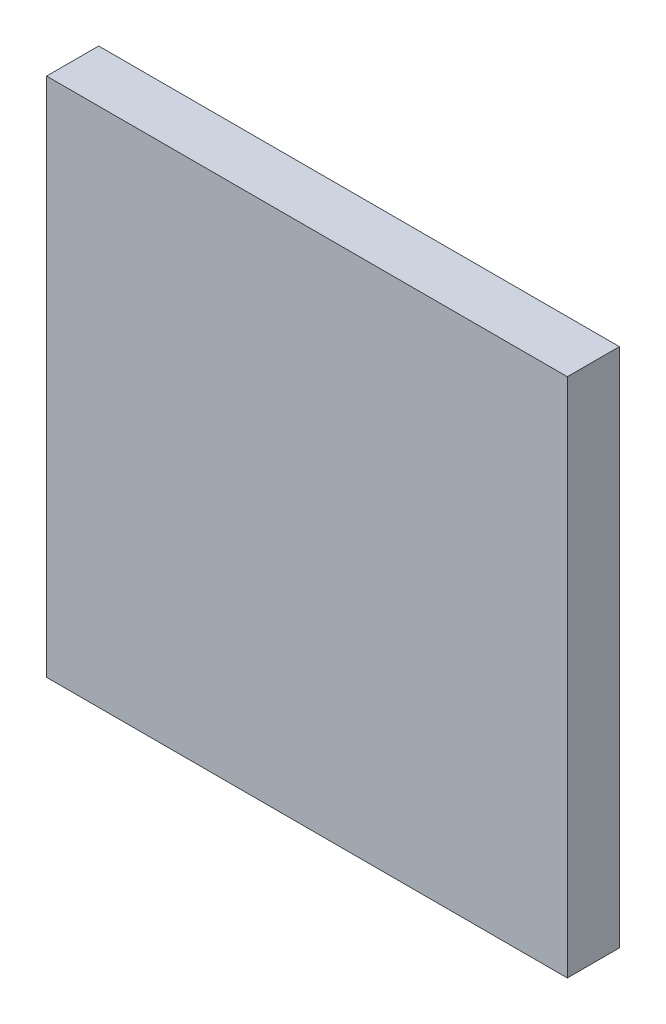
SolidWorks part; units mm, degrees
ref_plane "Plan de face" through (0, 0, 0) normal (0, 0, 1) x (1, 0, 0)
ref_plane "Plan de dessus" through (0, 0, 0) normal (0, 1, 0) x (1, 0, 0)
ref_plane "Plan de droite" through (0, 0, 0) normal (1, 0, 0) x (0, 0, -1)
sketch "Esquisse1" plane through (0, 0, 0) normal (0, 0, 1) x (1, 0, 0)
  line L1 (0, 0) -> (30, 0)
  line L2 (0, 0) -> (0, -30)
  line L3 (0, -30) -> (30, -30)
  line L4 (30, 0) -> (30, -30)
  dimension "D1" = 30
  dimension "D2" = 30
extrude "Boss.-Extru.1" add sketch "Esquisse1" along normal blind 3
ref_plane "Plan1" through (15, 0, 0) normal (-1, 0, 0) x (0, 0, 1)
sketch "Esquisse4" plane through (15, 0, 0) normal (-1, 0, 0) x (0, 0, 1)
  line L0 (0, 0) -> (0, -30) construction
  line L1 (0, -12.1733) -> (0, -13.6733)
  line L2 (0, -16.84) -> (0, -18.34)
  arc A0 (0, -12.1733) -> (0, -18.34) centre (-2.5481, -15.2567) ccw
  arc A1 (0, -13.6733) -> (0, -16.84) centre (-2.5481, -15.2567) ccw
  point P4 (0, 0)
  point P6 (0, 0)
  point P7 (0, 0)
  point P8 (-0.8317, -13.8771)
  point P9 (0, 0)
  point P10 (0, 0)
  point P11 (0, 0)
  point P14 (0, 0)
  point P15 (0, 0)
  point P16 (0, 0)
  dimension "D1" = 4
  dimension "D2" = 3
  dimension "D3" = 1.5
extrude "Boss.-Extru.2" add sketch "Esquisse4" along normal mid plane 5
